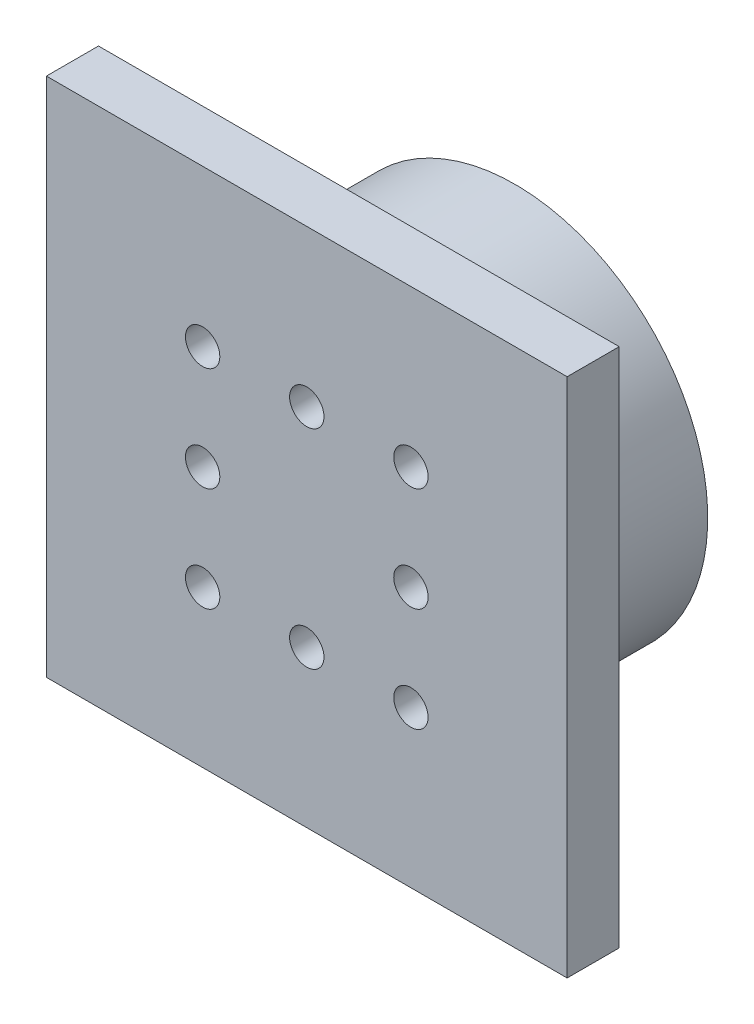
SolidWorks part; units mm, degrees
ref_plane "前视基准面" through (0, 0, 0) normal (0, 0, 1) x (1, 0, 0)
ref_plane "上视基准面" through (0, 0, 0) normal (0, 1, 0) x (1, 0, 0)
ref_plane "右视基准面" through (0, 0, 0) normal (1, 0, 0) x (0, 0, -1)
sketch "草图1" plane through (0, 0, 0) normal (0, 0, 1) x (1, 0, 0)
  line L0 (0, 5.4298) -> (0, 0) construction
  line L1 (-25, 25) -> (25, 25)
  line L2 (-25, 25) -> (-25, -25)
  line L3 (-25, -25) -> (25, -25)
  line L4 (25, 25) -> (25, -25)
  line L5 (-25, 25) -> (25, -25) construction
  line L6 (-25, -25) -> (25, 25) construction
  line L7 (0, 0) -> (8.6042, 0) construction
  circle A0 centre (-10, 10) radius 1.65
  circle A1 centre (0, 10) radius 1.65
  circle A2 centre (-10, 0) radius 1.65
  circle A3 centre (-10, -10) radius 1.65
  circle A4 centre (0, -10) radius 1.65
  circle A5 centre (10, -10) radius 1.65
  circle A6 centre (10, 0) radius 1.65
  circle A7 centre (10, 10) radius 1.65
  point P0 (0, 0)
  dimension "D3" = 3.3
  dimension "D4" = 3.3
  dimension "D5" = 3.3
  dimension "D1" = 50
  dimension "D2" = 50
  dimension "D6" = 10
  dimension "D7" = 10
  dimension "D8" = 10
extrude "凸台-拉伸1" add sketch "草图1" along normal blind 5
sketch "草图4" plane through (0, 0, 0) normal (0, 0, -1) x (-1, 0, 0)
  circle A0 centre (0, 0) radius 18.5
  circle A3 centre (10, -10) radius 1.65
  circle A4 centre (10, -10) radius 1.65
  circle A6 centre (0, -10) radius 1.65
  circle A7 centre (0, -10) radius 1.65
  circle A9 centre (-10, -10) radius 1.65
  circle A10 centre (-10, -10) radius 1.65
  circle A12 centre (10, 0) radius 1.65
  circle A13 centre (10, 0) radius 1.65
  circle A15 centre (-10, 0) radius 1.65
  circle A16 centre (-10, 0) radius 1.65
  circle A18 centre (10, 10) radius 1.65
  circle A19 centre (10, 10) radius 1.65
  circle A21 centre (0, 10) radius 1.65
  circle A22 centre (0, 10) radius 1.65
  circle A23 centre (0, 0) radius 5
  circle A24 centre (-10, 10) radius 1.65
  circle A25 centre (-10, 10) radius 1.65
  dimension "D1" = 37
  dimension "D10" = 10
  dimension "D2" = 0
  dimension "D3" = 0
  dimension "D4" = 0
  dimension "D5" = 0
  dimension "D6" = 0
  dimension "D7" = 0
  dimension "D8" = 0
  dimension "D9" = 0
extrude "凸台-拉伸4" add sketch "草图4" along normal blind 15
